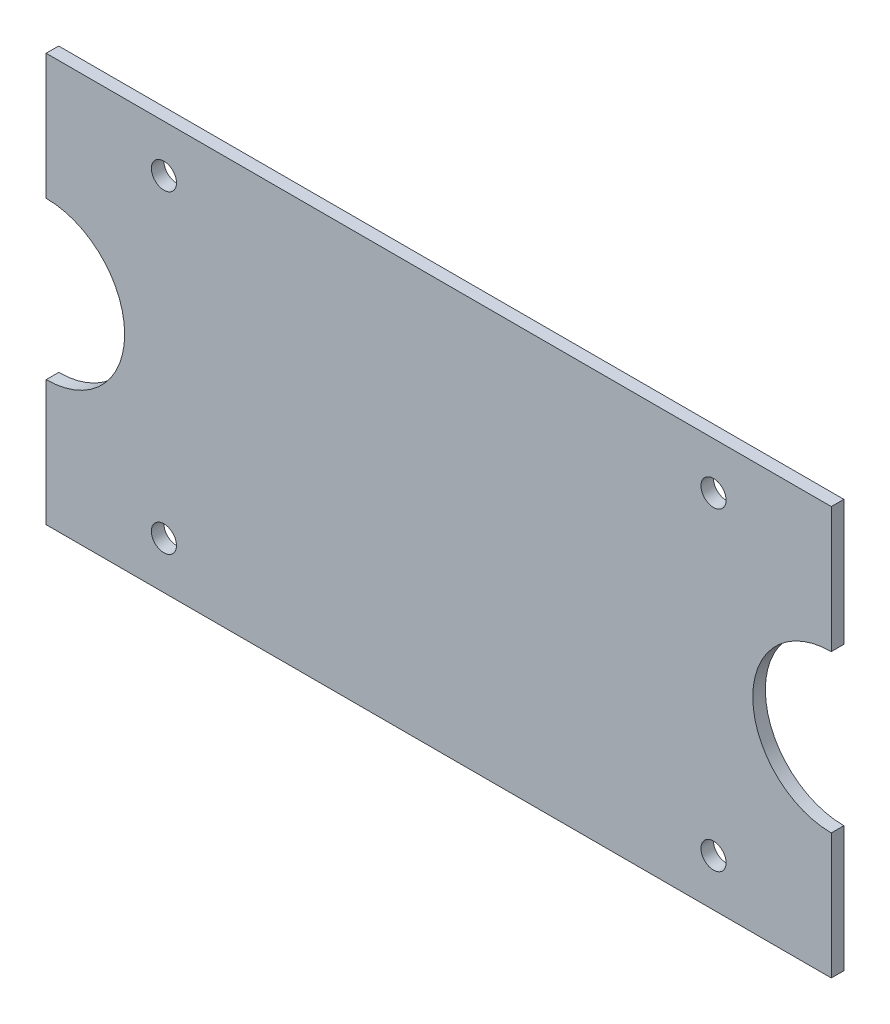
SolidWorks part; units mm, degrees
ref_plane "Plan de face" through (0, 0, 0) normal (0, 0, 1) x (1, 0, 0)
ref_plane "Plan de dessus" through (0, 0, 0) normal (0, 1, 0) x (1, 0, 0)
ref_plane "Plan de droite" through (0, 0, 0) normal (1, 0, 0) x (0, 0, -1)
sketch "Esquisse1" plane through (0, 0, 0) normal (0, 0, 1) x (1, 0, 0)
  line L0 (50, 52) -> (50, 46) construction
  line L1 (0, 0) -> (100, 0)
  line L2 (0, 0) -> (0, 52)
  line L3 (0, 52) -> (100, 52)
  line L4 (100, 0) -> (100, 52)
  line L5 (15, 46) -> (85, 46) construction
  line L6 (15, 46) -> (15, 6) construction
  line L7 (15, 6) -> (85, 6) construction
  line L8 (85, 46) -> (85, 6) construction
  line L9 (15, 26) -> (0, 26) construction
  circle A0 centre (15, 46) radius 1.6
  circle A1 centre (85, 46) radius 1.6
  circle A2 centre (15, 6) radius 1.6
  circle A3 centre (85, 6) radius 1.6
  dimension "D3" = 3.2
  dimension "D1" = 100
  dimension "D2" = 52
  dimension "D4" = 40
  dimension "D5" = 70
extrude "Boss.-Extru.1" add sketch "Esquisse1" along normal blind 1.6
sketch "Esquisse2" plane through (0, 0, 0) normal (0, 0, -1) x (-1, 0, 0)
  line L0 (-100, 0) -> (-100, 52) construction
  line L2 (0, 52) -> (0, 0) construction
  circle A0 centre (-100, 26) radius 10
  circle A1 centre (0, 26) radius 10
  point P4 (-100, 26)
  point P5 (0, 26)
  dimension "D1" = 20
extrude "Enlèv. mat.-Extru.1" cut sketch "Esquisse2" against normal through all
